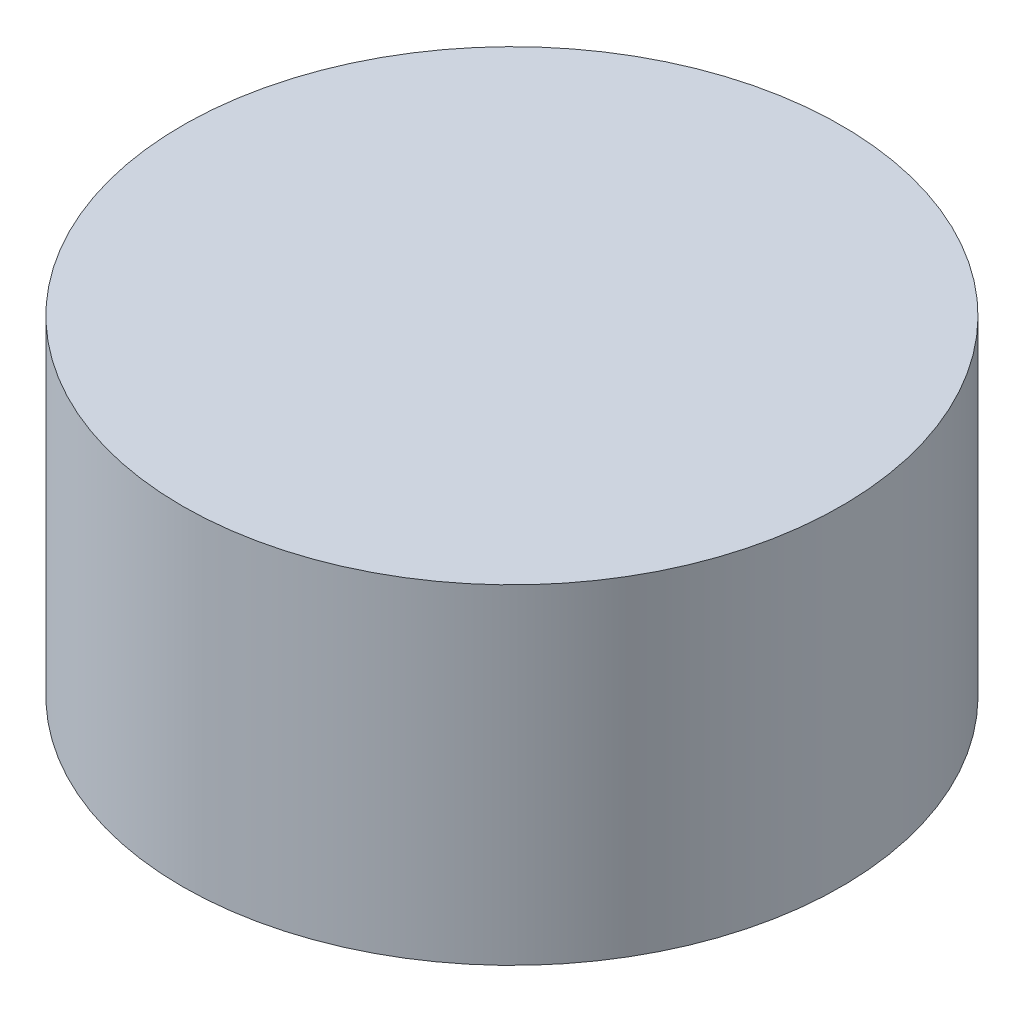
SolidWorks part; units mm, degrees
ref_plane "Front Plane" through (0, 0, 0) normal (0, 0, 1) x (1, 0, 0)
ref_plane "Top Plane" through (0, 0, 0) normal (0, 1, 0) x (1, 0, 0)
ref_plane "Right Plane" through (0, 0, 0) normal (1, 0, 0) x (0, 0, -1)
sketch "Sketch1" plane through (0, 0, 0) normal (0, 1, 0) x (1, 0, 0)
  circle A0 centre (0, 0) radius 6.35
  dimension "D1" = 12.7
extrude "Boss-Extrude1" add sketch "Sketch1" along normal blind 6.35
